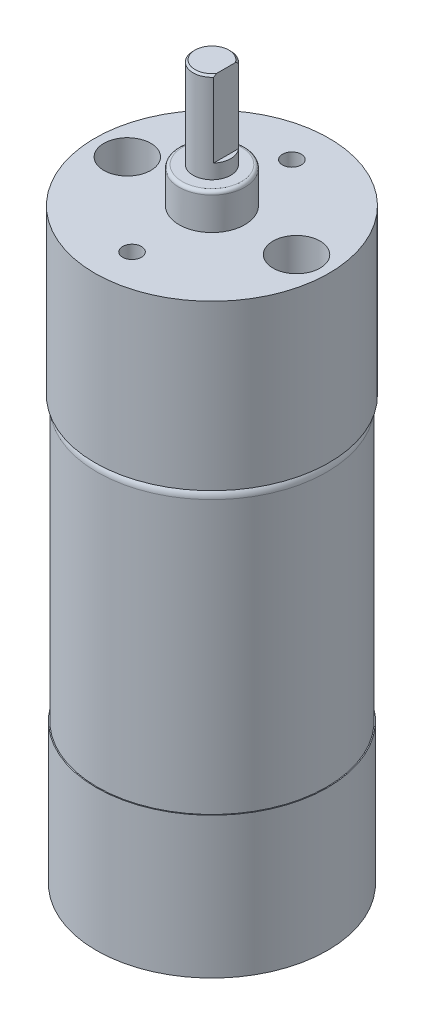
SolidWorks part; units mm, degrees
ref_plane "Alzado" through (0, 0, 0) normal (0, 0, 1) x (1, 0, 0)
ref_plane "Planta" through (0, 0, 0) normal (0, 1, 0) x (1, 0, 0)
ref_plane "Vista lateral" through (0, 0, 0) normal (1, 0, 0) x (0, 0, -1)
sketch "Croquis1" plane through (0, 0, 0) normal (0, 1, 0) x (1, 0, 0)
  circle A0 centre (0, 0) radius 12.3
  dimension "D1" = 24.6
extrude "Saliente-Extruir1" add sketch "Croquis1" along normal blind 15
sketch "Croquis2" plane through (0, 15, 0) normal (0, 1, 0) x (1, 0, 0)
  circle A0 centre (0, 0) radius 12.2
  dimension "D1" = 24.4
extrude "Saliente-Extruir2" add sketch "Croquis2" along normal blind 30 separate body
fillet "Redondeo1" radius 1 1 edges at (0, 45, 12.2)
sketch "Croquis3" plane through (0, 45, 0) normal (0, 1, 0) x (1, 0, 0)
  circle A0 centre (0, 0) radius 12.45
  dimension "D1" = 24.9
extrude "Saliente-Extruir3" add sketch "Croquis3" along normal blind 17.45
sketch "Croquis4" plane through (0, 62.45, 0) normal (0, 1, 0) x (1, 0, 0)
  line L0 (0, 0) -> (3.5743, 0) construction
  line L1 (0, 0) -> (0, 3.3853) construction
  circle A0 centre (0, 8.5) radius 1
  circle A1 centre (0, -8.5) radius 1
  circle A2 centre (9, 0) radius 2.5
  circle A3 centre (-9, 0) radius 2.5
  point P5 (0, 0)
  dimension "D1" = 8.5
  dimension "D2" = 2
  dimension "D3" = 5
  dimension "D4" = 9
extrude "Cortar-Extruir1" cut sketch "Croquis4" against normal blind 8
sketch "Croquis5" plane through (0, 62.45, 0) normal (0, 1, 0) x (1, 0, 0)
  circle A0 centre (0, 0) radius 3.5
  dimension "D1" = 7
extrude "Saliente-Extruir4" add sketch "Croquis5" along normal blind 3.8
fillet "Redondeo2" radius 0.35 1 edges at (0, 66.25, 3.5)
sketch "Croquis6" plane through (0, 66.25, 0) normal (0, 1, 0) x (1, 0, 0)
  circle A0 centre (0, 0) radius 2
  dimension "D1" = 4
extrude "Saliente-Extruir5" add sketch "Croquis6" along normal blind 9.64
chamfer "Chaflán1" distance 0.2 angle 45 1 edges at (0, 75.89, 2)
sketch "Croquis7" plane through (0, 75.89, 0) normal (0, 1, 0) x (1, 0, 0)
  line L0 (1.5, 1.3229) -> (1.5, -1.3229)
  arc A0 (1.5, -1.3229) -> (1.5, 1.3229) centre (0, 0) ccw
  dimension "D1" = 4
  dimension "D2" = 1.5
extrude "Cortar-Extruir2" cut sketch "Croquis7" against normal blind 8.1
